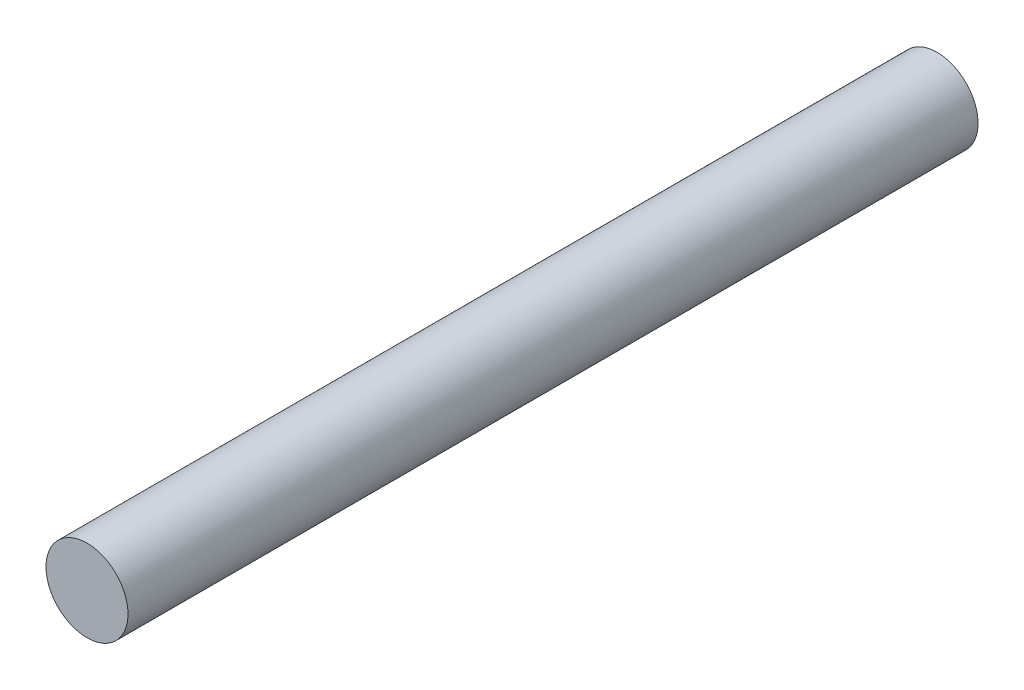
SolidWorks part; units mm, degrees
ref_plane "前视基准面" through (0, 0, 0) normal (0, 0, 1) x (1, 0, 0)
ref_plane "上视基准面" through (0, 0, 0) normal (0, 1, 0) x (1, 0, 0)
ref_plane "右视基准面" through (0, 0, 0) normal (1, 0, 0) x (0, 0, -1)
sketch "草图1" plane through (0, 0, 0) normal (0, 0, 1) x (1, 0, 0)
  circle A0 centre (0, 0) radius 2.75
extrude "凸台-拉伸1" add sketch "草图1" along normal blind 57
